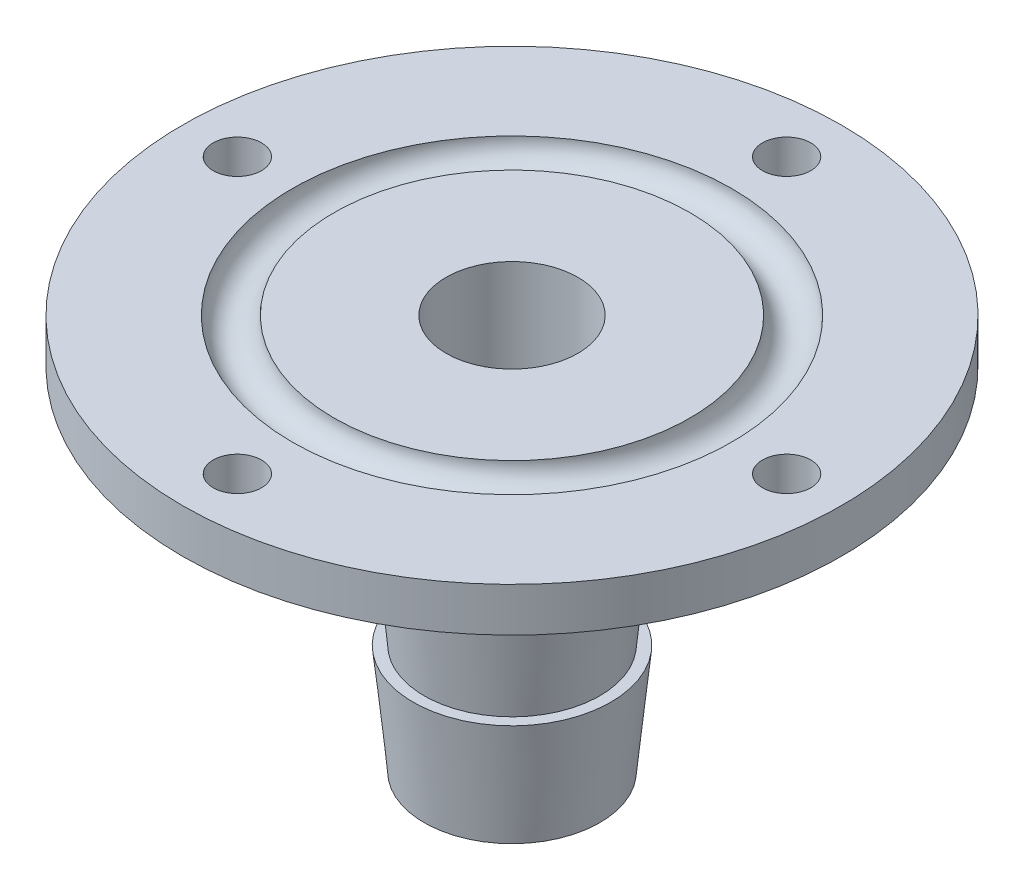
SolidWorks part; units mm, degrees
ref_plane "前视基准面" through (0, 0, 0) normal (0, 0, 1) x (1, 0, 0)
ref_plane "上视基准面" through (0, 0, 0) normal (0, 1, 0) x (1, 0, 0)
ref_plane "右视基准面" through (0, 0, 0) normal (1, 0, 0) x (0, 0, -1)
sketch "草图1" plane through (0, 0, 0) normal (0, 1, 0) x (1, 0, 0)
  circle A0 centre (0, 0) radius 15
  circle A1 centre (0, 0) radius 3
  dimension "D1" = 6
  dimension "D2" = 30
extrude "凸台-拉伸1" add sketch "草图1" along normal blind 2
sketch "草图2" plane through (0, 0, 0) normal (0, 0, 1) x (1, 0, 0)
  line L0 (-15, 2) -> (15, 2) construction
  line L1 (0, 2) -> (0, 77.4048) construction
  circle A0 centre (9.05, 2) radius 0.95
  dimension "D1" = 1.9
  dimension "D2" = 9.05
revolve "切除-旋转1" cut sketch "草图2" angle 360 about L1
sketch "草图3" plane through (0, 2, 0) normal (0, 1, 0) x (1, 0, 0)
  line L0 (-15, 0) -> (15, 0) construction
  line L1 (0, 15) -> (0, -15) construction
  circle A0 centre (0, 0) radius 15 construction
  circle A1 centre (12.5, 0) radius 1.1
  circle A2 centre (0, -12.5) radius 1.1
  circle A3 centre (-12.5, 0) radius 1.1
  circle A4 centre (0, 12.5) radius 1.1
  point P18 (0, 0)
  dimension "D1" = 2.2
  dimension "D2" = 12.5
  dimension "D3" = 4
extrude "切除-拉伸1" cut sketch "草图3" against normal up to next
sketch "草图4" plane through (0, 0, 0) normal (1, 0, 0) x (0, 0, -1)
  line L0 (0, 0) -> (0, -10.6437) construction
  line L1 (-15, 0) -> (15, 0) construction
  line L2 (0, 0) -> (4, 0)
  line L3 (4, 0) -> (4, -1)
  line L4 (4, -16) -> (0, -16)
  line L5 (0, -16) -> (0, 0)
  line L6 (4, -16) -> (4.5, -11)
  line L7 (4.5, -11) -> (4, -11)
  line L8 (4.5, -6) -> (4, -6)
  line L9 (4, -11) -> (4.5, -6)
  line L10 (4.5, -1) -> (4, -1)
  line L11 (4, -6) -> (4.5, -1)
  dimension "D1" = 4.5
  dimension "D2" = 4
  dimension "D3" = 5
  dimension "D4" = 3
  dimension "D6" = 16
revolve "旋转1" add sketch "草图4" angle 360 about L5
sketch "草图5" plane through (0, 0, 0) normal (0, 1, 0) x (1, 0, 0)
  circle A1 centre (0, 0) radius 3
  circle A2 centre (0, 0) radius 3
  dimension "D1" = 0
extrude "切除-拉伸2" cut sketch "草图5" against normal up to next
